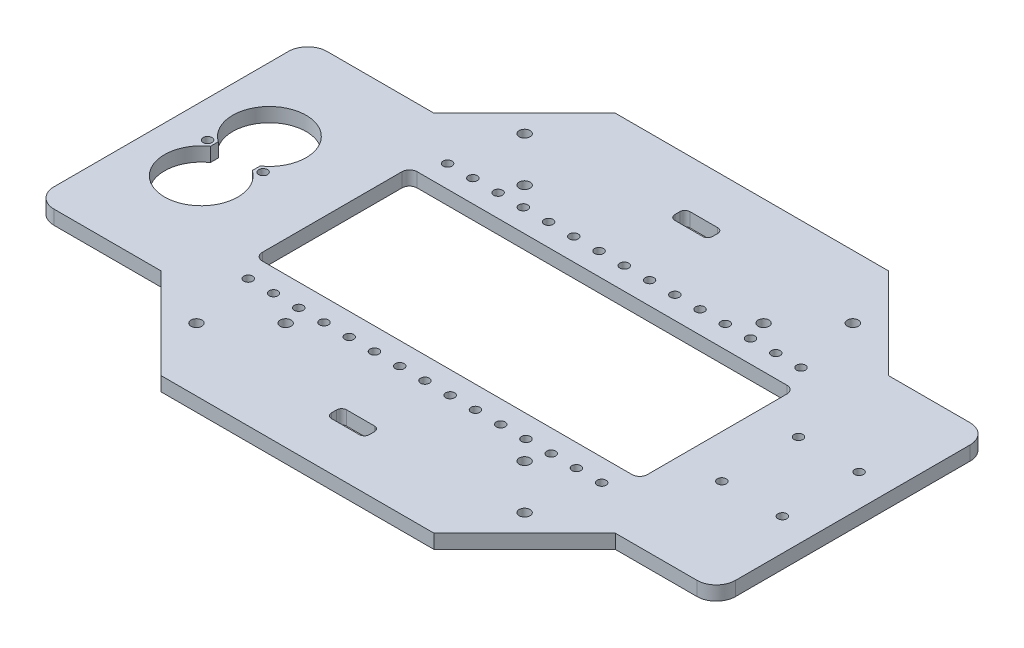
SolidWorks part; units mm, degrees
ref_plane "Front Plane" through (0, 0, 0) normal (0, 0, 1) x (1, 0, 0)
ref_plane "Top Plane" through (0, 0, 0) normal (0, 1, 0) x (1, 0, 0)
ref_plane "Right Plane" through (0, 0, 0) normal (1, 0, 0) x (0, 0, -1)
sketch "Sketch1" plane through (0, 0, 0) normal (0, 1, 0) x (1, 0, 0)
  line L0 (-73.2542, 28.5227) -> (-37.3332, 64.4437)
  line L1 (-37.3332, 64.4437) -> (70.8248, 64.4437)
  line L2 (70.8248, 64.4437) -> (106.7458, 28.5227)
  line L3 (106.7458, 28.5227) -> (106.7458, -79.6353)
  line L4 (106.7458, -79.6353) -> (70.8248, -115.5563)
  line L5 (70.8248, -115.5563) -> (-37.3332, -115.5563)
  line L6 (-37.3332, -115.5563) -> (-73.2542, -79.6353)
  line L7 (-73.2542, -79.6353) -> (-73.2542, 28.5227)
  dimension "D1" = 180
  dimension "D2" = 50.8
  dimension "D3" = 180
extrude "Boss-Extrude1" add sketch "Sketch1" along normal blind 5.588
sketch "Sketch2" plane through (0, 5.588, 0) normal (0, 1, 0) x (1, 0, 0)
  line L0 (-48.2542, 39.4437) -> (81.7458, 39.4437) construction
  line L1 (81.7458, 39.4437) -> (81.7458, -90.5563) construction
  line L2 (81.7458, -90.5563) -> (-48.2542, -90.5563) construction
  line L3 (-48.2542, -90.5563) -> (-48.2542, 39.4437) construction
  line L4 (-30.581, 21.7706) -> (64.0727, 21.7706) construction
  line L5 (64.0727, 21.7706) -> (64.0727, -72.8831) construction
  line L6 (64.0727, -72.8831) -> (-30.581, -72.8831) construction
  line L7 (-30.581, -72.8831) -> (-30.581, 21.7706) construction
  line L8 (-48.2542, 39.4437) -> (-30.581, 21.7706) construction
  line L9 (64.0727, 21.7706) -> (81.7458, 39.4437) construction
  line L10 (-48.2542, -90.5563) -> (-30.581, -72.8831) construction
  line L11 (64.0727, -72.8831) -> (81.7458, -90.5563) construction
  line L12 (-73.2542, -25.5563) -> (-48.2542, -25.5563) construction
  line L13 (-73.2542, 28.5227) -> (-73.2542, -79.6353) construction
  line L14 (16.7458, 39.4437) -> (16.7458, 64.4437) construction
  line L15 (70.8248, 64.4437) -> (-37.3332, 64.4437) construction
  line L19 (81.7458, -25.5563) -> (106.7458, -25.5563) construction
  line L20 (106.7458, -79.6353) -> (106.7458, 28.5227) construction
  line L21 (16.7458, -90.5563) -> (16.7458, -115.5563) construction
  line L22 (-37.3332, -115.5563) -> (70.8248, -115.5563) construction
  circle A0 centre (-48.2542, 39.4437) radius 2.159
  circle A1 centre (-30.581, 21.7706) radius 2.159
  circle A2 centre (-48.2542, -90.5563) radius 2.159
  circle A3 centre (-30.581, -72.8831) radius 2.159
  circle A4 centre (64.0727, 21.7706) radius 2.159
  circle A5 centre (81.7458, 39.4437) radius 2.159
  circle A6 centre (64.0727, -72.8831) radius 2.159
  circle A7 centre (81.7458, -90.5563) radius 2.159
  dimension "D1" = 4.318
  dimension "D2" = 24.9936
  dimension "D3" = 130
  dimension "D4" = 94.6537
extrude "Cut-Extrude1" cut sketch "Sketch2" against normal through all
sketch "Sketch3" plane through (0, 5.588, 0) normal (0, 1, 0) x (1, 0, 0)
  line L5 (-59.5092, 5.1137) -> (93.0008, 5.1137)
  line L6 (-59.5092, 5.1137) -> (-59.5092, -56.2263)
  line L7 (-59.5092, -56.2263) -> (93.0008, -56.2263)
  line L12 (93.0008, 5.1137) -> (93.0008, -56.2263)
  line L16 (-73.2542, -25.5563) -> (106.7458, -25.5563) construction
  line L17 (-73.2542, 28.5227) -> (-73.2542, -79.6353) construction
  line L18 (106.7458, -79.6353) -> (106.7458, 28.5227) construction
  line L19 (16.7458, -115.5563) -> (16.7458, 64.4437) construction
  line L20 (-37.3332, -115.5563) -> (70.8248, -115.5563) construction
  line L21 (70.8248, 64.4437) -> (-37.3332, 64.4437) construction
  dimension "D2" = 152.51
  dimension "D4" = 61.34
extrude "Cut-Extrude2" cut sketch "Sketch3" against normal through all
sketch "Sketch5" plane through (0, 5.588, 0) normal (0, 1, 0) x (1, 0, 0)
  line L1 (-73.2542, -79.6353) -> (-115.6342, -79.6353)
  line L2 (-73.2542, -79.6353) -> (-73.2542, 28.5227)
  line L3 (-73.2542, 28.5227) -> (-115.6342, 28.5227)
  line L4 (-123.2542, -72.0153) -> (-123.2542, 20.9027)
  arc A0 (-115.6342, -79.6353) -> (-123.2542, -72.0153) centre (-115.6342, -72.0153) cw
  arc A1 (-123.2542, 20.9027) -> (-115.6342, 28.5227) centre (-115.6342, 20.9027) cw
  point P10 (-123.2542, 28.5227)
  dimension "D2" = 7.62
  dimension "D1" = 50
extrude "Boss-Extrude2" add sketch "Sketch5" against normal up to surface (5.588 mm away) up to face at (16.7458, 0, 25.5563)
sketch "Sketch6" plane through (0, 5.588, 0) normal (0, 1, 0) x (1, 0, 0)
  line L1 (106.7458, 28.5227) -> (139.1258, 28.5227)
  line L2 (106.7458, 28.5227) -> (106.7458, -79.6353)
  line L3 (106.7458, -79.6353) -> (139.1258, -79.6353)
  line L4 (146.7458, 20.9027) -> (146.7458, -72.0153)
  arc A0 (139.1258, 28.5227) -> (146.7458, 20.9027) centre (139.1258, 20.9027) cw
  arc A1 (146.7458, -72.0153) -> (139.1258, -79.6353) centre (139.1258, -72.0153) cw
  point P8 (146.7458, 28.5227)
  dimension "D2" = 7.62
  dimension "D1" = 40
extrude "Boss-Extrude3" add sketch "Sketch6" against normal up to surface (5.588 mm away) up to face at (16.7458, 0, 25.5563)
sketch "Sketch7" plane through (0, 5.588, 0) normal (0, 1, 0) x (1, 0, 0)
  line L0 (110.0458, -40.7563) -> (110.0458, -10.3563) construction
  line L1 (110.0458, -10.3563) -> (134.0458, -10.3563) construction
  line L2 (134.0458, -10.3563) -> (134.0458, -40.7563) construction
  line L3 (134.0458, -40.7563) -> (110.0458, -40.7563) construction
  line L4 (-123.2542, -25.5563) -> (146.7458, -25.5563) construction
  line L5 (-123.2542, 20.9027) -> (-123.2542, -72.0153) construction
  line L6 (146.7458, -72.0153) -> (146.7458, 20.9027) construction
  circle A0 centre (110.0458, -10.3563) radius 1.75
  circle A1 centre (134.0458, -10.3563) radius 1.75
  circle A2 centre (110.0458, -40.7563) radius 1.75
  circle A3 centre (134.0458, -40.7563) radius 1.75
  dimension "D3" = 3.5
  dimension "D1" = 24
  dimension "D2" = 30.4
  dimension "D4" = 12.7
extrude "Cut-Extrude4" cut sketch "Sketch7" against normal through all
sketch "Sketch8" plane through (0, 5.588, 0) normal (0, 1, 0) x (1, 0, 0)
  line L0 (-106.1542, -24.0067) -> (-106.1542, -27.1059)
  line L1 (-89.5542, -24.0067) -> (-89.5542, -27.1059)
  line L2 (-97.8542, -12.0563) -> (-97.8542, -39.0563) construction
  line L3 (-123.2542, -25.5563) -> (146.7458, -25.5563) construction
  line L4 (-123.2542, 20.9027) -> (-123.2542, -72.0153) construction
  line L5 (146.7458, -72.0153) -> (146.7458, 20.9027) construction
  arc A0 (-106.1542, -27.1059) -> (-89.5542, -27.1059) centre (-97.8542, -39.0563) ccw
  arc A1 (-89.5542, -24.0067) -> (-106.1542, -24.0067) centre (-97.8542, -12.0563) ccw
  circle A2 centre (-108.8542, -25.5563) radius 1.75
  circle A3 centre (-86.8542, -25.5563) radius 1.75
  dimension "D1" = 29.1
  dimension "D5" = 3.5
  dimension "D2" = 27
  dimension "D3" = 16.6
  dimension "D4" = 22
  dimension "D6" = 25.4
extrude "Cut-Extrude6" cut sketch "Sketch8" against normal through all
sketch "Sketch9" plane through (0, 5.588, 0) normal (0, 1, 0) x (1, 0, 0)
  line L2 (16.7458, 64.4437) -> (16.7458, -115.5563) construction
  line L3 (70.8248, 64.4437) -> (-37.3332, 64.4437) construction
  line L4 (-37.3332, -115.5563) -> (70.8248, -115.5563) construction
  line L5 (93.0008, 5.1137) -> (-59.5092, 5.1137) construction
  line L6 (-123.2542, -25.5563) -> (146.7458, -25.5563) construction
  line L7 (-123.2542, 20.9027) -> (-123.2542, -72.0153) construction
  line L8 (146.7458, -72.0153) -> (146.7458, 20.9027) construction
  circle A0 centre (-53.2542, 13.9237) radius 1.75
  circle A1 centre (-43.2542, 13.9237) radius 1.75
  circle A2 centre (-33.2542, 13.9237) radius 1.75
  circle A3 centre (-23.2542, 13.9237) radius 1.75
  circle A4 centre (-13.2542, 13.9237) radius 1.75
  circle A5 centre (-3.2542, 13.9237) radius 1.75
  circle A6 centre (6.7458, 13.9237) radius 1.75
  circle A7 centre (16.7458, 13.9237) radius 1.75
  circle A8 centre (26.7458, 13.9237) radius 1.75
  circle A9 centre (36.7458, 13.9237) radius 1.75
  circle A10 centre (46.7458, 13.9237) radius 1.75
  circle A11 centre (56.7458, 13.9237) radius 1.75
  circle A12 centre (66.7458, 13.9237) radius 1.75
  circle A13 centre (76.7458, 13.9237) radius 1.75
  circle A14 centre (86.7458, 13.9237) radius 1.75
  circle A15 centre (-53.2542, -65.0363) radius 1.75
  circle A16 centre (-43.2542, -65.0363) radius 1.75
  circle A17 centre (-33.2542, -65.0363) radius 1.75
  circle A18 centre (-23.2542, -65.0363) radius 1.75
  circle A19 centre (-13.2542, -65.0363) radius 1.75
  circle A20 centre (-3.2542, -65.0363) radius 1.75
  circle A21 centre (6.7458, -65.0363) radius 1.75
  circle A22 centre (16.7458, -65.0363) radius 1.75
  circle A23 centre (26.7458, -65.0363) radius 1.75
  circle A24 centre (36.7458, -65.0363) radius 1.75
  circle A25 centre (46.7458, -65.0363) radius 1.75
  circle A26 centre (56.7458, -65.0363) radius 1.75
  circle A27 centre (66.7458, -65.0363) radius 1.75
  circle A28 centre (76.7458, -65.0363) radius 1.75
  circle A29 centre (86.7458, -65.0363) radius 1.75
  dimension "D1" = 3.5
  dimension "D4" = 3.5
  dimension "D3" = 8.81
  dimension "D6" = 78.96
  dimension "D7" = 140
  dimension "D8" = 10
  dimension "D2" = 15
  dimension "D5" = 15
extrude "Cut-Extrude8" cut sketch "Sketch9" against normal through all
sketch "Sketch10" plane through (0, 5.588, 0) normal (0, 1, 0) x (1, 0, 0)
  line L0 (-123.2542, -25.5563) -> (146.7458, -25.5563) construction
  line L1 (11.2458, 45.4437) -> (22.2458, 45.4437)
  line L2 (9.2458, 43.4437) -> (9.2458, 41.4437)
  line L3 (11.2458, 39.4437) -> (22.2458, 39.4437)
  line L4 (24.2458, 43.4437) -> (24.2458, 41.4437)
  line L5 (11.2458, -90.5563) -> (22.2458, -90.5563)
  line L6 (9.2458, -92.5563) -> (9.2458, -94.5563)
  line L7 (11.2458, -96.5563) -> (22.2458, -96.5563)
  line L8 (24.2458, -92.5563) -> (24.2458, -94.5563)
  line L9 (-123.2542, 20.9027) -> (-123.2542, -72.0153) construction
  line L10 (146.7458, -72.0153) -> (146.7458, 20.9027) construction
  line L11 (16.7458, -115.5563) -> (16.7458, 64.4437) construction
  line L12 (-37.3332, -115.5563) -> (70.8248, -115.5563) construction
  line L13 (70.8248, 64.4437) -> (-37.3332, 64.4437) construction
  arc A0 (9.2458, -94.5563) -> (11.2458, -96.5563) centre (11.2458, -94.5563) ccw
  arc A1 (22.2458, -96.5563) -> (24.2458, -94.5563) centre (22.2458, -94.5563) ccw
  arc A2 (24.2458, -92.5563) -> (22.2458, -90.5563) centre (22.2458, -92.5563) ccw
  arc A3 (11.2458, -90.5563) -> (9.2458, -92.5563) centre (11.2458, -92.5563) ccw
  arc A4 (9.2458, 41.4437) -> (11.2458, 39.4437) centre (11.2458, 41.4437) ccw
  arc A5 (22.2458, 39.4437) -> (24.2458, 41.4437) centre (22.2458, 41.4437) ccw
  arc A6 (24.2458, 43.4437) -> (22.2458, 45.4437) centre (22.2458, 43.4437) ccw
  arc A7 (11.2458, 45.4437) -> (9.2458, 43.4437) centre (11.2458, 43.4437) ccw
  point P32 (24.2458, 39.4437)
  point P35 (24.2458, 45.4437)
  point P38 (9.2458, 45.4437)
  dimension "D4" = 2
  dimension "D1" = 15
  dimension "D2" = 6
  dimension "D3" = 65
extrude "Cut-Extrude9" cut sketch "Sketch10" against normal through all
fillet "Fillet1" radius 3 4 edges at (-59.5092, 2.794, 56.2263) (93.0008, 2.794, 56.2263) (93.0008, 2.794, -5.1137) (-59.5092, 2.794, -5.1137)
